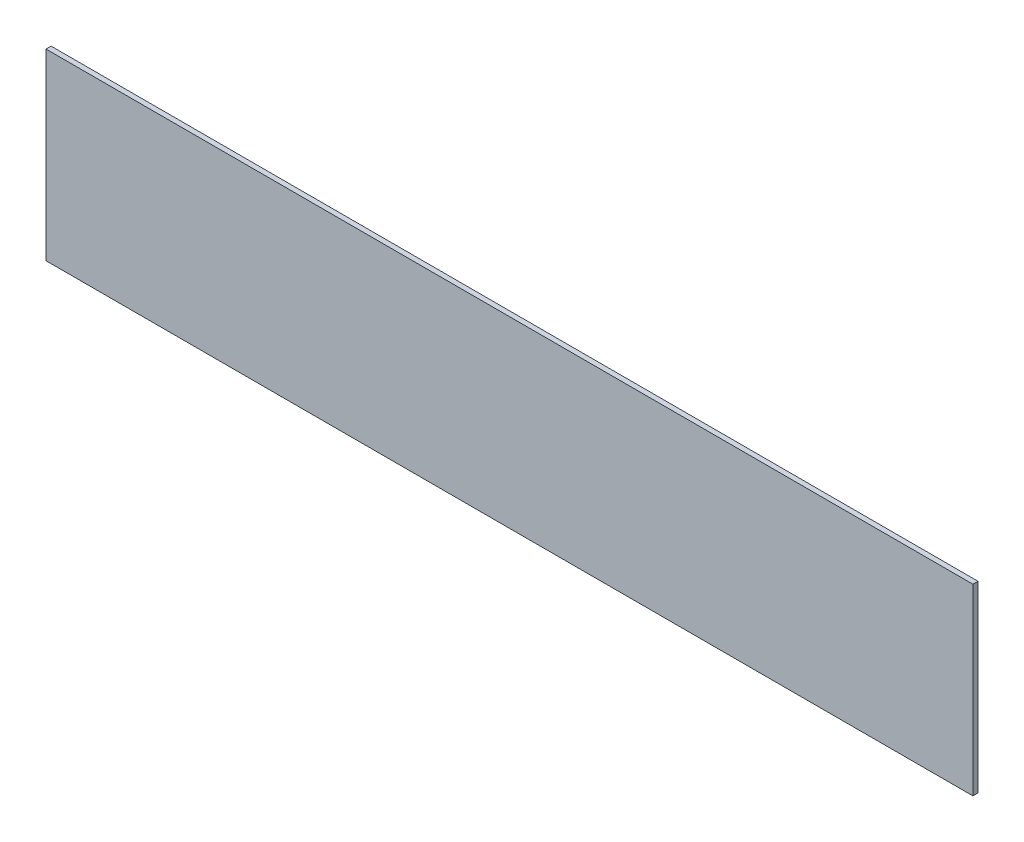
SolidWorks part; units mm, degrees
ref_plane "Front Plane" through (0, 0, 0) normal (0, 0, 1) x (1, 0, 0)
ref_plane "Top Plane" through (0, 0, 0) normal (0, 1, 0) x (1, 0, 0)
ref_plane "Right Plane" through (0, 0, 0) normal (1, 0, 0) x (0, 0, -1)
other "Configuration Table"
sketch "Sketch1" plane through (0, 0, 0) normal (0, 0, 1) x (1, 0, 0)
  line L1 (259, 927) -> (441, 927)
  line L2 (259, 927) -> (259, 963)
  line L3 (259, 963) -> (441, 963)
  line L4 (441, 927) -> (441, 963)
extrude "TOPPING_klape_kat3_kulp_cukuru_1" add sketch "Sketch1" along normal blind 1 from offset 26 separate body
